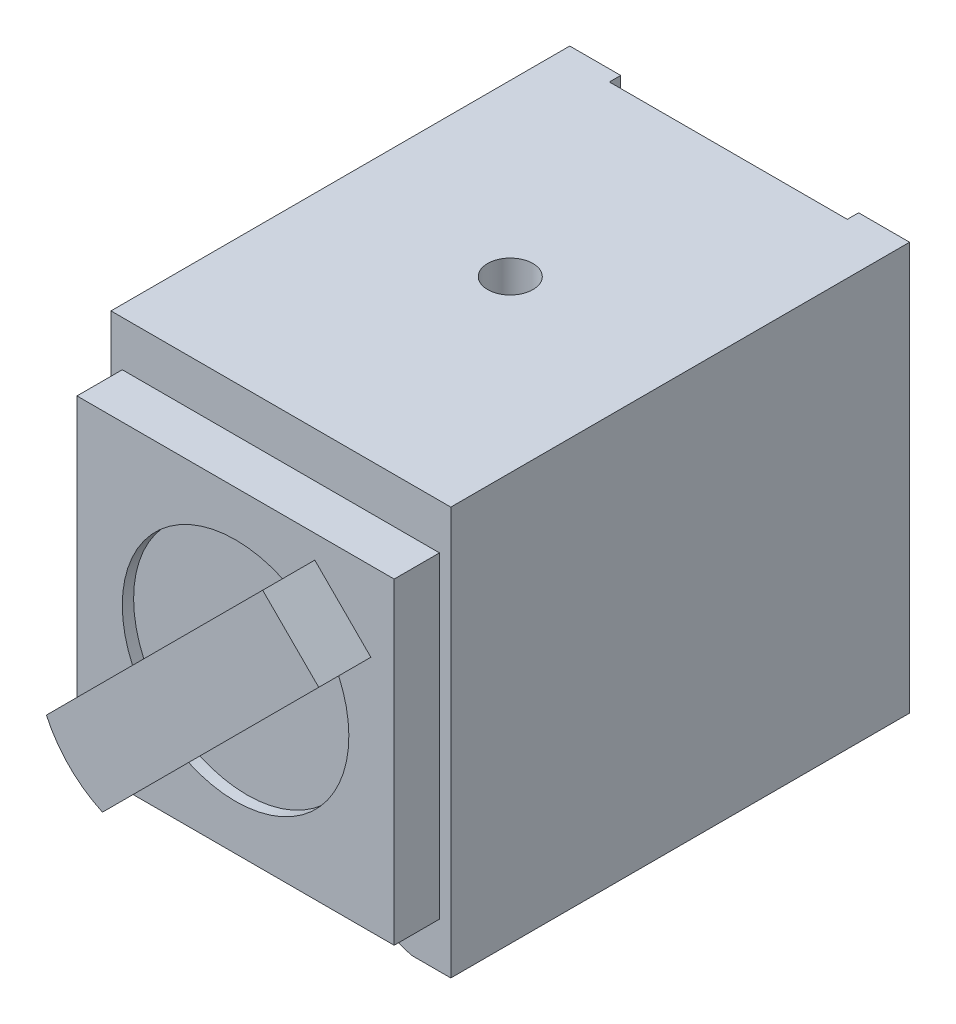
SolidWorks part; units mm, degrees
ref_plane "前视基准面" through (0, 0, 0) normal (0, 0, 1) x (1, 0, 0)
ref_plane "上视基准面" through (0, 0, 0) normal (0, 1, 0) x (1, 0, 0)
ref_plane "右视基准面" through (0, 0, 0) normal (1, 0, 0) x (0, 0, -1)
sketch "草图1" plane through (0, 0, 0) normal (0, 1, 0) x (1, 0, 0)
  line L1 (-15, 20.25) -> (15, 20.25)
  line L2 (-15, 20.25) -> (-15, -20.25)
  line L3 (-15, -20.25) -> (15, -20.25)
  line L4 (15, 20.25) -> (15, -20.25)
  line L5 (0, -20.25) -> (0, 20.25) construction
  line L6 (-15, 0) -> (15, 0) construction
  point P36 (0, 0)
  dimension "D1" = 30
  dimension "D2" = 40.5
extrude "凸台-拉伸1" add sketch "草图1" along normal blind 36
sketch "草图2" plane through (0, 0, 20.25) normal (0, 0, 1) x (1, 0, 0)
  line L0 (-15, 36) -> (15, 36) construction
  line L1 (-14, 32) -> (14, 32)
  line L2 (-14, 32) -> (-14, 4)
  line L3 (-14, 4) -> (14, 4)
  line L4 (14, 32) -> (14, 4)
  line L5 (0, 4) -> (0, 32) construction
  line L6 (-14, 18) -> (14, 18) construction
  point P132 (0, 18)
  dimension "D1" = 4
  dimension "D2" = 28
  dimension "D3" = 28
extrude "凸台-拉伸2" add sketch "草图2" along normal blind 4
sketch "草图3" plane through (0, 0, 24.25) normal (0, 0, 1) x (1, 0, 0)
  line L0 (0, 32) -> (0, 4) construction
  line L1 (14, 32) -> (-14, 32) construction
  line L2 (-14, 4) -> (14, 4) construction
  line L3 (-14, 18) -> (14, 18) construction
  line L4 (-14, 32) -> (-14, 4) construction
  line L5 (14, 4) -> (14, 32) construction
  circle A0 centre (0, 18) radius 10
  dimension "D1" = 20
extrude "切除-拉伸1" cut sketch "草图3" against normal blind 1
sketch "草图5" plane through (0, 0, 23.25) normal (0, 0, 1) x (1, 0, 0)
  line L0 (0, 18) -> (11.6302, 29.6302) construction
  line L1 (0, 18) -> (22.1837, 18) construction
  line L2 (4.1489, 27.0987) -> (-9.0987, 13.8511)
  line L3 (9.0987, 22.1489) -> (-4.1489, 8.9013)
  circle A0 centre (0, 18) radius 10 construction
  circle A1 centre (0, 18) radius 10 construction
  arc A2 (-9.0987, 13.8511) -> (-4.1489, 8.9013) centre (0, 18) ccw
  arc A3 (9.0987, 22.1489) -> (4.1489, 27.0987) centre (0, 18) ccw
  dimension "D1" = 45
  dimension "D2" = 7
extrude "凸台-拉伸3" add sketch "草图5" along normal blind 4
sketch "草图6" plane through (0, 0, 27.25) normal (0, 0, 1) x (1, 0, 0)
  line L0 (-9.0987, 13.8511) -> (9.9932, 32.9429)
  line L1 (-4.1489, 8.9013) -> (14.9429, 27.9932)
  line L2 (4.1489, 27.0987) -> (-9.0987, 13.8511) construction
  line L3 (-4.1489, 8.9013) -> (9.0987, 22.1489) construction
  line L4 (-9.0987, 13.8511) -> (-4.1489, 8.9013) construction
  line L5 (9.9932, 32.9429) -> (14.9429, 27.9932)
  arc A0 (-9.0987, 13.8511) -> (-4.1489, 8.9013) centre (0, 18) ccw construction
  arc A1 (-9.0987, 13.8511) -> (-4.1489, 8.9013) centre (0, 18) ccw
  dimension "D1" = 10
  dimension "D2" = 27
extrude "凸台-拉伸4" add sketch "草图6" along normal blind 4.6
sketch "草图7" plane through (0, 36, 0) normal (0, 1, 0) x (1, 0, 0)
  line L0 (15, 20.25) -> (-15, 20.25) construction
  line L1 (-10.5, 20.25) -> (10.5, 20.25)
  line L2 (-10.5, 20.25) -> (-10.5, 19.25)
  line L3 (-10.5, 19.25) -> (10.5, 19.25)
  line L4 (10.5, 20.25) -> (10.5, 19.25)
  line L5 (0, 19.25) -> (0, 20.25) construction
  line L6 (-10.5, 19.75) -> (10.5, 19.75) construction
  line L7 (15, -20.25) -> (15, 20.25) construction
  point P96 (0, 19.75)
  dimension "D1" = 4.5
  dimension "D2" = 1
extrude "切除-拉伸2" cut sketch "草图7" against normal through all
sketch "草图8" plane through (0, 0, 20.25) normal (0, 0, 1) x (1, 0, 0)
  line L0 (-15, 0) -> (-11.5, 0) construction
  line L1 (-15, 0) -> (15, 0) construction
  line L2 (-11.5, 0) -> (-3, 3)
  line L3 (-3, 3) -> (3, 3)
  line L4 (0, 3) -> (0, 0) construction
  line L5 (-11.5, 0) -> (11.5, 0)
  line L6 (11.5, 0) -> (3, 3)
  dimension "D1" = 3.5
  dimension "D2" = 3
  dimension "D3" = 3
extrude "切除-拉伸3" cut sketch "草图8" against normal through all
sketch "草图9" plane through (0, 36, 0) normal (0, 1, 0) x (1, 0, 0)
  circle A0 centre (0, 0) radius 2
  dimension "D1" = 4
extrude "切除-拉伸4" cut sketch "草图9" against normal blind 6.5
cosmetic thread "装饰螺纹线1" parameters "D2"=5
